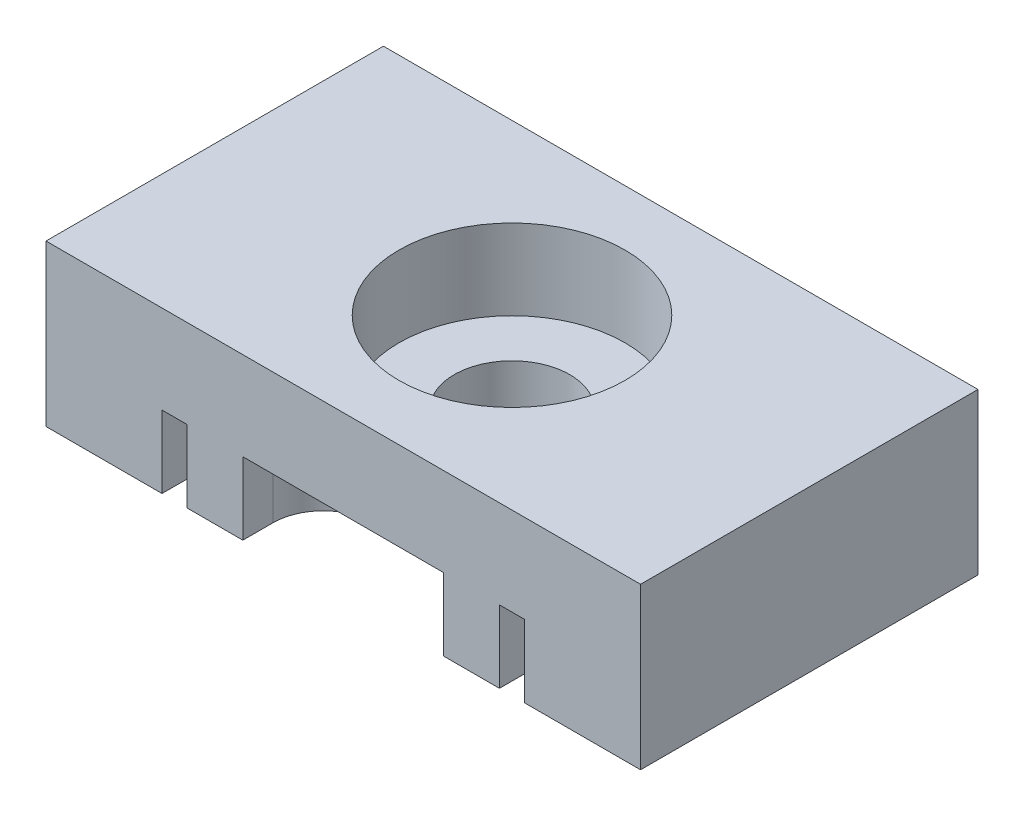
SolidWorks part; units mm, degrees
material "Nylon 6/10"
ref_plane "Front Plane" through (0, 0, 0) normal (0, 0, 1) x (1, 0, 0)
ref_plane "Top Plane" through (0, 0, 0) normal (0, 1, 0) x (1, 0, 0)
ref_plane "Right Plane" through (0, 0, 0) normal (1, 0, 0) x (0, 0, -1)
sketch "Sketch1" plane through (0, 0, 0) normal (0, 1, 0) x (1, 0, 0)
  line L1 (-9.398, -5.334) -> (9.398, -5.334)
  line L2 (-9.398, -5.334) -> (-9.398, 5.334)
  line L3 (-9.398, 5.334) -> (9.398, 5.334)
  line L4 (9.398, -5.334) -> (9.398, 5.334)
  line L5 (-9.398, -5.334) -> (9.398, 5.334) construction
  line L6 (-9.398, 5.334) -> (9.398, -5.334) construction
  point P0 (0, 0)
  dimension "D1" = 18.796
  dimension "D2" = 10.668
extrude "Base" add sketch "Sketch1" along normal blind 5.08
sketch "Sketch2" plane through (0, 0, 0) normal (0, -1, 0) x (1, 0, 0)
  line L0 (-5.334, 5.334) -> (-5.334, 3.8608) construction
  line L1 (-9.398, 5.334) -> (9.398, 5.334) construction
  line L2 (-4.9371, 5.334) -> (-4.9371, 3.8608)
  line L3 (-5.7309, 5.334) -> (-5.7309, 3.8608)
  line L4 (5.334, 5.334) -> (5.334, 3.8608) construction
  line L5 (5.7309, 5.334) -> (5.7309, 3.8608)
  line L6 (4.9371, 5.334) -> (4.9371, 3.8608)
  line L7 (0, 0) -> (0, 225.9023) construction
  arc A0 (-4.9371, 5.334) -> (-5.7309, 5.334) centre (-5.334, 5.334) ccw
  arc A1 (-5.7309, 3.8608) -> (-4.9371, 3.8608) centre (-5.334, 3.8608) ccw
  arc A2 (5.7309, 5.334) -> (4.9371, 5.334) centre (5.334, 5.334) ccw
  arc A3 (4.9371, 3.8608) -> (5.7309, 3.8608) centre (5.334, 3.8608) ccw
  point P4 (-5.334, 4.5974)
  point P9 (5.334, 4.5974)
  dimension "D1" = 0.7937
  dimension "D2" = 10.668
  dimension "D3" = 1.4732
extrude "BoxSlots" cut sketch "Sketch2" against normal blind 2.286
hole_wizard "MoutingHole" positions "Sketch6" profile "Sketch5" counterbore size "#6" standard "ANSI Inch" end condition through all
sketch "Sketch6" plane through (0, 5.08, 0) normal (0, 1, 0) x (1, 0, 0)
  point P0 (0, 0)
sketch "Sketch5" plane through (0, 5.08, 0) normal (1, 0, 0) x (0, 0, 1)
  line L0 (0, 0) -> (0, 5.08)
  line L1 (0, 5.08) -> (1.8288, 5.08)
  line L3 (1.8288, 5.08) -> (1.8288, 2.54)
  line L4 (1.8288, 2.54) -> (3.5725, 2.54)
  line L5 (3.5725, 2.54) -> (3.5725, 0)
  line L7 (3.5725, 0) -> (0, 0)
  line L11 (0, -6.35) -> (0, 107.95) construction
  dimension "Thru Hole Dia." = 3.6576
  dimension "Thru Hole Depth" = 5.08
  dimension "C'Bore Dia." = 7.145
  dimension "C'Bore Depth" = 2.54
sketch "Sketch7" plane through (0, 0, 0) normal (0, -1, 0) x (1, 0, 0)
  line L0 (-4.9371, 5.334) -> (4.9371, 5.334) construction
  line L1 (-3.175, 5.334) -> (3.175, 5.334)
  line L2 (-3.175, 5.334) -> (-3.175, 4.3815)
  line L3 (-1.5875, 2.794) -> (1.5875, 2.794)
  line L4 (3.175, 5.334) -> (3.175, 4.3815)
  line L5 (-3.175, 5.334) -> (3.175, 2.794) construction
  line L6 (-3.175, 2.794) -> (3.175, 5.334) construction
  arc A0 (-1.5875, 2.794) -> (-3.175, 4.3815) centre (-1.5875, 4.3815) cw
  arc A1 (1.5875, 2.794) -> (3.175, 4.3815) centre (1.5875, 4.3815) ccw
  point P0 (0, 4.064)
  dimension "D3" = 1.5875
  dimension "D1" = 6.35
  dimension "D2" = 2.54
extrude "Cut-Extrude1" cut sketch "Sketch7" against normal blind 2.286
